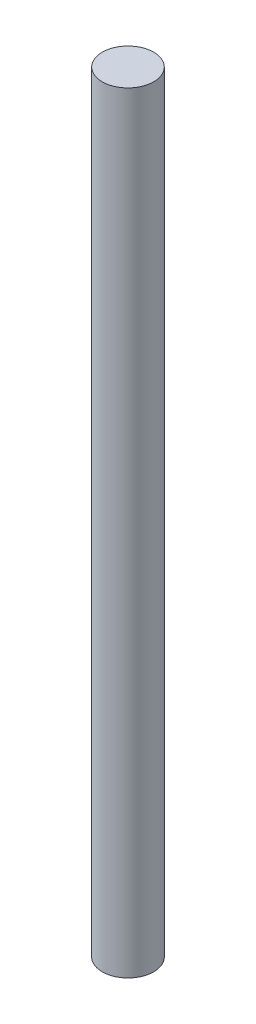
SolidWorks part; units mm, degrees
ref_plane "Front Plane" through (0, 0, 0) normal (0, 0, 1) x (1, 0, 0)
ref_plane "Top Plane" through (0, 0, 0) normal (0, 1, 0) x (1, 0, 0)
ref_plane "Right Plane" through (0, 0, 0) normal (1, 0, 0) x (0, 0, -1)
sketch "Sketch1" plane through (0, 0, 0) normal (0, 1, 0) x (1, 0, 0)
  circle A0 centre (0, 0) radius 4
  dimension "D1" = 8
extrude "Boss-Extrude1" add sketch "Sketch1" along normal blind 120
